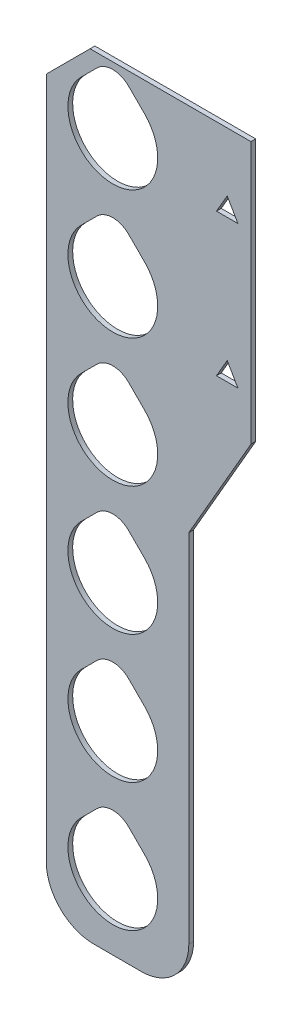
SolidWorks part; units mm, degrees
ref_plane "前视基准面" through (0, 0, 0) normal (0, 0, 1) x (1, 0, 0)
ref_plane "上视基准面" through (0, 0, 0) normal (0, 1, 0) x (1, 0, 0)
ref_plane "右视基准面" through (0, 0, 0) normal (1, 0, 0) x (0, 0, -1)
sketch "草图1" plane through (0, 0, 0) normal (0, 0, 1) x (1, 0, 0)
  line L0 (-3.3411, 10.0232) -> (-6.6822, 6.6822)
  line L1 (6.6822, 6.6822) -> (3.3411, 10.0232)
  line L2 (29.0767, 92.6495) -> (29.0767, 147.8038)
  line L3 (29.0767, 147.8038) -> (-4.7766, 147.8038)
  line L4 (-4.7766, 147.8038) -> (-14, 138.5805)
  line L5 (-14, 138.5805) -> (-14, -5)
  line L6 (-4, -15) -> (6, -15)
  line L7 (16, -5) -> (16, 70)
  line L8 (16, 70) -> (29.0767, 92.6495)
  line L9 (-3.3411, 37.0232) -> (-6.6822, 33.6822)
  line L10 (6.6822, 33.6822) -> (3.3411, 37.0232)
  line L11 (6.6822, 60.6822) -> (3.3411, 64.0232)
  line L12 (-3.3411, 64.0232) -> (-6.6822, 60.6822)
  line L13 (-3.3411, 91.0232) -> (-6.6822, 87.6822)
  line L21 (6.6822, 87.6822) -> (3.3411, 91.0232)
  line L22 (6.6822, 141.6822) -> (3.3411, 145.0232)
  line L23 (-3.3411, 145.0232) -> (-6.6822, 141.6822)
  line L24 (-3.3411, 118.0232) -> (-6.6822, 114.6822)
  line L25 (6.6822, 114.6822) -> (3.3411, 118.0232)
  line L26 (26.3284, 101.5038) -> (24.0767, 105.4038)
  line L27 (21.825, 101.5038) -> (26.3284, 101.5038)
  line L28 (24.0767, 105.4038) -> (21.825, 101.5038)
  line L29 (21.825, 131.5038) -> (26.3284, 131.5038)
  line L30 (24.0767, 135.4038) -> (21.825, 131.5038)
  line L31 (26.3284, 131.5038) -> (24.0767, 135.4038)
  arc A0 (-14, -5) -> (-4, -15) centre (-4, -5) ccw
  arc A1 (6, -15) -> (16, -5) centre (6, -5) ccw
  arc A2 (-6.6822, 6.6822) -> (6.6822, 6.6822) centre (0, 0) ccw
  arc A3 (3.3411, 10.0232) -> (-3.3411, 10.0232) centre (0, 6.6822) ccw
  arc A6 (3.3411, 37.0232) -> (-3.3411, 37.0232) centre (0, 33.6822) ccw
  arc A7 (-6.6822, 33.6822) -> (6.6822, 33.6822) centre (0, 27) ccw
  arc A8 (-6.6822, 60.6822) -> (6.6822, 60.6822) centre (0, 54) ccw
  arc A9 (3.3411, 64.0232) -> (-3.3411, 64.0232) centre (0, 60.6822) ccw
  arc A10 (3.3411, 91.0232) -> (-3.3411, 91.0232) centre (0, 87.6822) ccw
  arc A11 (-6.6822, 87.6822) -> (6.6822, 87.6822) centre (0, 81) ccw
  arc A12 (3.3411, 145.0232) -> (-3.3411, 145.0232) centre (0, 141.6822) ccw
  arc A13 (-6.6822, 141.6822) -> (6.6822, 141.6822) centre (0, 135) ccw
  arc A14 (3.3411, 118.0232) -> (-3.3411, 118.0232) centre (0, 114.6822) ccw
  arc A15 (-6.6822, 114.6822) -> (6.6822, 114.6822) centre (0, 108) ccw
extrude "凸台-拉伸1" add sketch "草图1" along normal blind 1 contours L6 A1 L7 L8 L2 L3 L4 L5 A0 A15 L24 A14 L25 A13 L23 A12 L22 A11 L13 A10 L21 A9 L11 A8 L12 A7 L9 A6 L10 A3 L1 A2 L0 L28 L26 L27 L31 L29 L30
